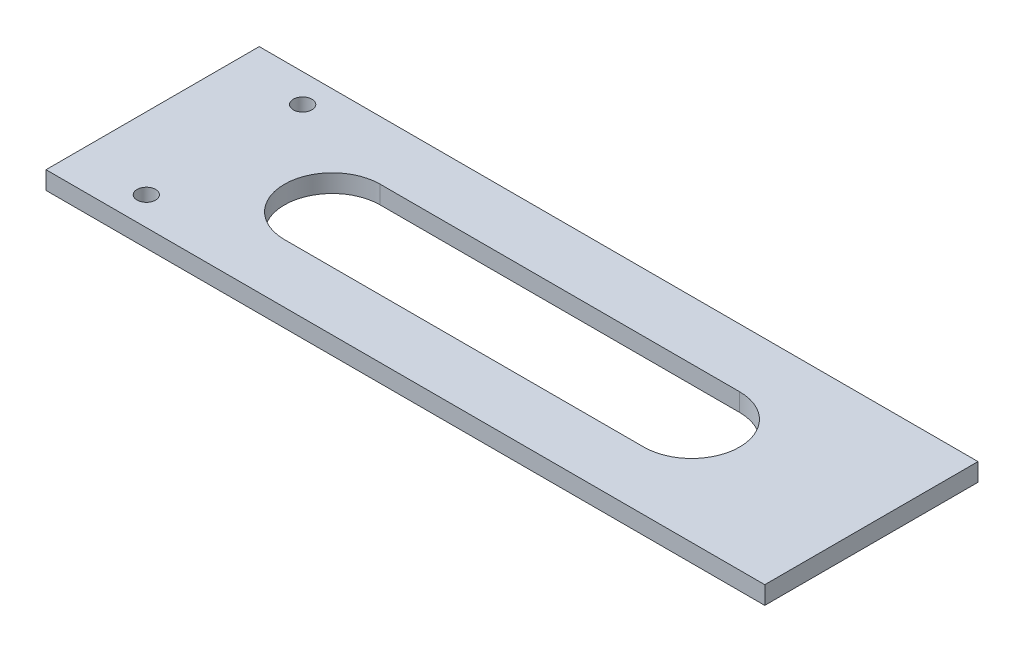
SolidWorks part; units mm, degrees
material "Thornel VCB-20 碳布"
ref_plane "前视基准面" through (0, 0, 0) normal (0, 0, 1) x (1, 0, 0)
ref_plane "上视基准面" through (0, 0, 0) normal (0, 1, 0) x (1, 0, 0)
ref_plane "右视基准面" through (0, 0, 0) normal (1, 0, 0) x (0, 0, -1)
other "Configuration Table"
sketch "草图1" plane through (0, 0, 0) normal (0, 1, 0) x (1, 0, 0)
  line L0 (30, 17.8) -> (90, 17.8) construction
  line L1 (0, 0) -> (120, 0)
  line L2 (0, 0) -> (0, 35.6)
  line L3 (0, 35.6) -> (120, 35.6)
  line L4 (120, 0) -> (120, 35.6)
  line L5 (30, 25.8) -> (90, 25.8)
  line L6 (30, 9.8) -> (90, 9.8)
  line L7 (120, 17.8) -> (0, 17.8) construction
  arc A0 (30, 25.8) -> (30, 9.8) centre (30, 17.8) ccw
  arc A1 (90, 9.8) -> (90, 25.8) centre (90, 17.8) ccw
  point P7 (60, 17.8)
  dimension "D3" = 8
  dimension "D1" = 120
  dimension "D2" = 35.6
  dimension "D4" = 60
  dimension "D5" = 60
extrude "凸台-拉伸1" add sketch "草图1" along normal blind 3
sketch "草图2" plane through (0, 0, 0) normal (0, -1, 0) x (1, 0, 0)
  circle A0 centre (138, -4.75) radius 1.55 construction
  circle A1 centre (138, -30.85) radius 1.55 construction
  circle A2 centre (138, -4.75) radius 1.55
  circle A3 centre (138, -30.85) radius 1.55
  circle A4 centre (12, -30.85) radius 1.55 construction
  circle A5 centre (12, -4.75) radius 1.55 construction
  circle A6 centre (12, -30.85) radius 1.55
  circle A7 centre (12, -4.75) radius 1.55
extrude "切除-拉伸1" cut sketch "草图2" against normal blind 3
